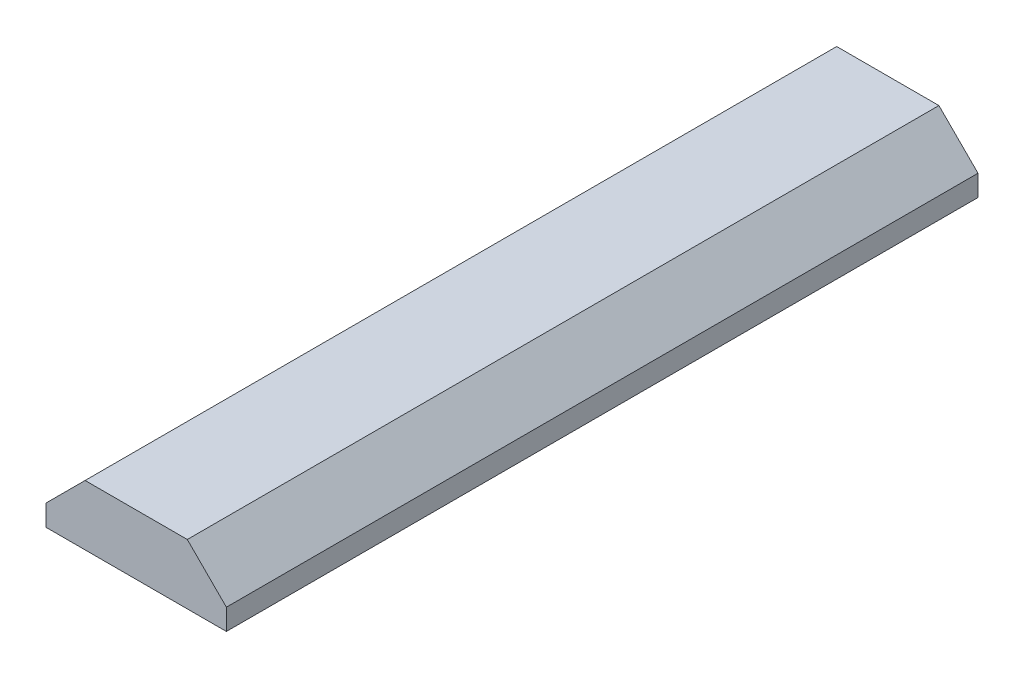
SolidWorks part; units mm, degrees
ref_plane "Ebene vorne" through (0, 0, 0) normal (0, 0, 1) x (1, 0, 0)
ref_plane "Ebene oben" through (0, 0, 0) normal (0, 1, 0) x (1, 0, 0)
ref_plane "Ebene rechts" through (0, 0, 0) normal (1, 0, 0) x (0, 0, -1)
sketch "Skizze1" plane through (0, 0, 0) normal (0, 0, 1) x (1, 0, 0)
  line L0 (0, 0) -> (0, 23680.6173) construction
  line L1 (3.4, 1.8089) -> (-3.4, 1.8089)
  line L2 (-3.4, 1.8089) -> (-6, -0.7911)
  line L3 (-6, -0.7911) -> (-6, -2.1911)
  line L4 (-6, -2.1911) -> (6, -2.1911)
  line L5 (6, -0.7911) -> (6, -2.1911)
  line L6 (3.4, 1.8089) -> (6, -0.7911)
  point P9 (0, -2.1911)
  point P11 (0, 1.8089)
  dimension "D1" = 3.4
  dimension "D2" = 6
  dimension "D3" = 4
  dimension "D4" = 135
extrude "Aufsatz-Linear austragen1" add sketch "Skizze1" along normal blind 50 contours L1 L2 L3 L4 L5 L6
